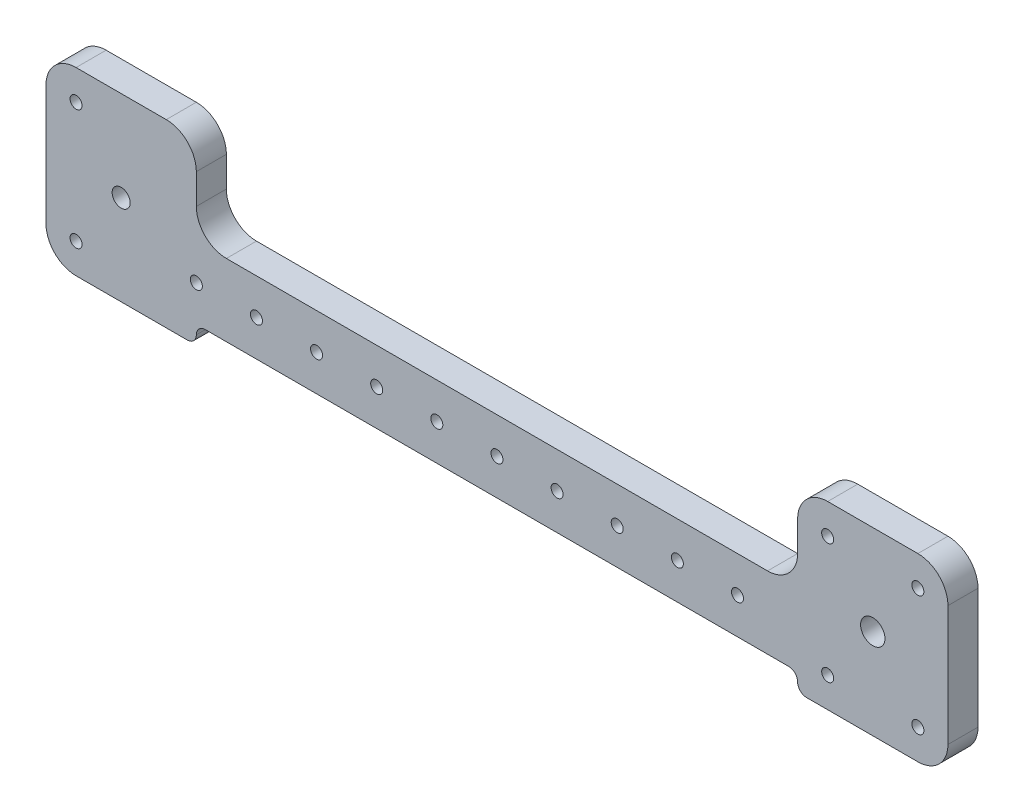
SolidWorks part; units mm, degrees
ref_plane "Front Plane" through (0, 0, 0) normal (0, 0, 1) x (1, 0, 0)
ref_plane "Top Plane" through (0, 0, 0) normal (0, 1, 0) x (1, 0, 0)
ref_plane "Right Plane" through (0, 0, 0) normal (1, 0, 0) x (0, 0, -1)
sketch "Model" plane through (0, 0, 0) normal (0, 0, 1) x (1, 0, 0)
  line L0 (-90.0894, 6) -> (103.9106, 6)
  line L1 (-103.0894, 60) -> (-133.0894, 60)
  line L2 (-93.0894, 40) -> (-93.0894, 50)
  line L3 (96.9106, 30) -> (-83.0894, 30)
  line L4 (106.9106, 50) -> (106.9106, 40)
  line L5 (146.9106, 60) -> (116.9106, 60)
  line L6 (156.9106, 10) -> (156.9106, 50)
  line L7 (109.9106, 0) -> (146.9106, 0)
  line L8 (-143.0894, 50) -> (-143.0894, 10)
  line L9 (-133.0894, 0) -> (-96.0894, 0)
  circle A0 centre (131.9106, 30) radius 4.05
  circle A1 centre (-118.0894, 30) radius 3
  circle A2 centre (6.9106, 18) radius 2
  circle A3 centre (-33.0894, 18) radius 2
  circle A4 centre (-13.0894, 18) radius 2
  circle A5 centre (86.9106, 18) radius 2
  circle A6 centre (66.9106, 18) radius 2
  circle A7 centre (46.9106, 18) radius 2
  circle A8 centre (26.9106, 18) radius 2
  circle A9 centre (146.9106, 10) radius 2
  circle A10 centre (146.9106, 50) radius 2
  circle A11 centre (-133.0894, 10) radius 2
  circle A12 centre (-133.0894, 50) radius 2
  circle A13 centre (-93.0894, 18) radius 2
  circle A14 centre (-73.0894, 18) radius 2
  circle A15 centre (-53.0894, 18) radius 2
  circle A16 centre (116.9106, 50) radius 2
  circle A17 centre (116.9106, 10) radius 2
  arc A18 (-143.0894, 10) -> (-133.0894, 0) centre (-133.0894, 10) ccw
  arc A19 (-133.0894, 60) -> (-143.0894, 50) centre (-133.0894, 50) ccw
  arc A20 (-93.0894, 50) -> (-103.0894, 60) centre (-103.0894, 50) ccw
  arc A21 (-93.0894, 40) -> (-83.0894, 30) centre (-83.0894, 40) ccw
  arc A22 (96.9106, 30) -> (106.9106, 40) centre (96.9106, 40) ccw
  arc A23 (116.9106, 60) -> (106.9106, 50) centre (116.9106, 50) ccw
  arc A24 (156.9106, 50) -> (146.9106, 60) centre (146.9106, 50) ccw
  arc A25 (146.9106, 0) -> (156.9106, 10) centre (146.9106, 10) ccw
  arc A26 (106.9106, 3) -> (109.9106, 0) centre (109.9106, 3) ccw
  arc A27 (106.9106, 3) -> (103.9106, 6) centre (103.9106, 3) ccw
  arc A28 (-90.0894, 6) -> (-93.0894, 3) centre (-90.0894, 3) ccw
  arc A29 (-96.0894, 0) -> (-93.0894, 3) centre (-96.0894, 3) ccw
extrude "Boss-Extrude1" add sketch "Model" along normal blind 10
sketch "Sketch2" plane through (0, 0, 10) normal (0, 0, 1) x (1, 0, 0)
  text T0 "Copyright © Adarsh Belavatagi and Manikanta Pujar 2018.\r\nThis documentation describes Open Hardware and is licensed under the CERN OHL v. 1.2. \r\nYou may redistribute and modify this documentation under the terms of the CERN OHL v.1.2. \r\n(http://ohwr.org/cernohl). This documentation is distributed WITHOUT ANY EXPRESS OR\r\n IMPLIED WARRANTY, INCLUDING OF MERCHANTABILITY, SATISFACTORY QUALITY AND FITNESS FOR A PARTICULAR PURPOSE.\r\n Please see the CERN OHL v.1.2 for applicable conditions\r\n\r\nThe full text of the license is available in LICENSE.txt(https://github.com/AdarshBelavatagi/Maudslay/blob/master/LICENSE.txt)"
